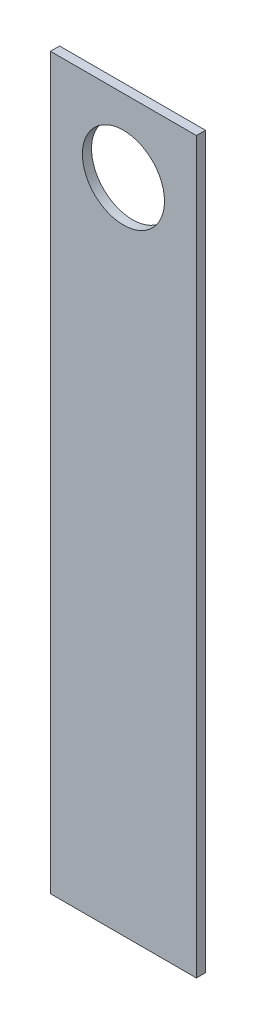
SolidWorks part; units mm, degrees
ref_plane "Front Plane" through (0, 0, 0) normal (0, 0, 1) x (1, 0, 0)
ref_plane "Top Plane" through (0, 0, 0) normal (0, 1, 0) x (1, 0, 0)
ref_plane "Right Plane" through (0, 0, 0) normal (1, 0, 0) x (0, 0, -1)
sketch "Sketch1" plane through (0, 0, 0) normal (0, 0, 1) x (1, 0, 0)
  line L0 (25.4, 254) -> (25.4, 228.6) construction
  line L1 (0, 0) -> (50.8, 0)
  line L2 (0, 0) -> (0, 254)
  line L3 (0, 254) -> (50.8, 254)
  line L4 (50.8, 0) -> (50.8, 254)
  line L5 (0, 0) -> (50.8, 254) construction
  line L6 (0, 254) -> (50.8, 0) construction
  circle A0 centre (25.4, 228.6) radius 14.2875
  point P4 (25.4, 127)
  dimension "D4" = 28.575
  dimension "D1" = 50.8
  dimension "D2" = 254
  dimension "D3" = 25.4
extrude "Boss-Extrude1" add sketch "Sketch1" along normal blind 3.175
